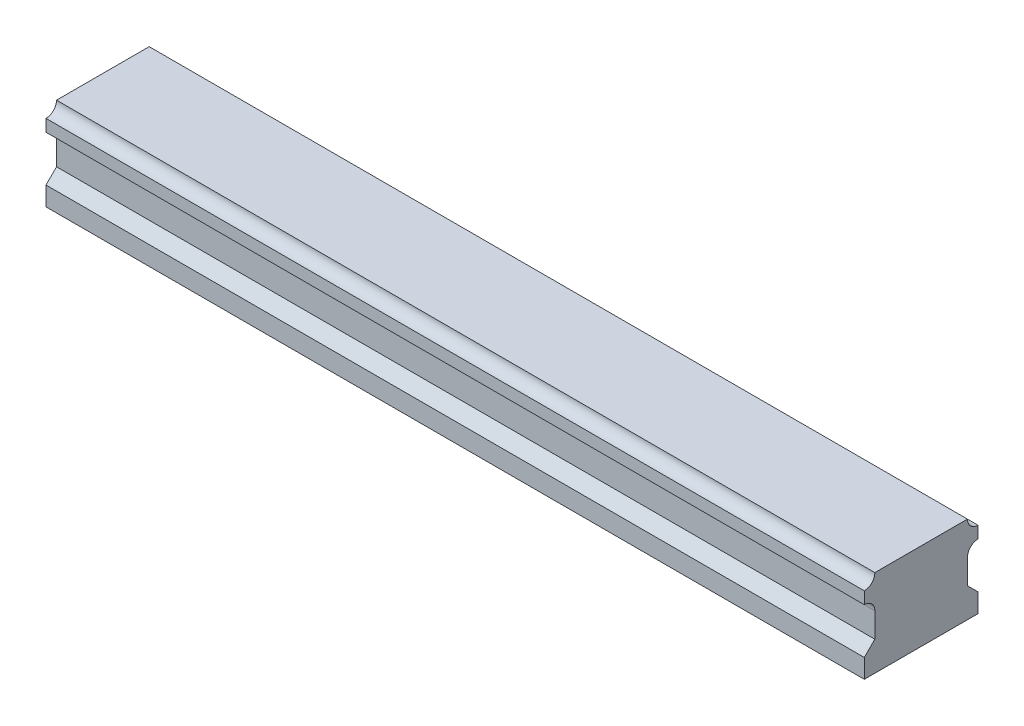
SolidWorks part; units mm, degrees
ref_plane "Front Plane" through (0, 0, 0) normal (0, 0, 1) x (1, 0, 0)
ref_plane "Top Plane" through (0, 0, 0) normal (0, 1, 0) x (1, 0, 0)
ref_plane "Right Plane" through (0, 0, 0) normal (1, 0, 0) x (0, 0, -1)
sketch "Sketch1" plane through (0, 0, 0) normal (1, 0, 0) x (0, 0, -1)
  line L0 (0, 0) -> (30, 0)
  line L1 (0, 0) -> (0, 5)
  line L2 (0, 5) -> (2.7781, 7.7781)
  line L3 (2.7781, 7.7781) -> (2.7781, 14.2781)
  line L4 (2.7781, 14.2781) -> (0, 14.2781) construction
  line L5 (0, 14.2781) -> (0, 23) construction
  line L6 (0, 23) -> (30, 23) construction
  line L12 (15, 0) -> (15, 23) construction
  line L13 (27.2219, 23) -> (2.7781, 23)
  line L14 (0, 20.2219) -> (0, 17.0562)
  line L15 (30, 14.2781) -> (30, 23) construction
  line L16 (27.2219, 14.2781) -> (30, 14.2781) construction
  line L17 (30, 20.2219) -> (30, 17.0562)
  line L18 (27.2219, 7.7781) -> (27.2219, 14.2781)
  line L19 (30, 5) -> (27.2219, 7.7781)
  line L20 (30, 0) -> (30, 5)
  arc A0 (2.7781, 14.2781) -> (0, 17.0562) centre (0, 14.2781) ccw
  arc A1 (0, 20.2219) -> (2.7781, 23) centre (0, 23) ccw
  arc A2 (30, 20.2219) -> (27.2219, 23) centre (30, 23) cw
  arc A3 (27.2219, 14.2781) -> (30, 17.0562) centre (30, 14.2781) cw
  dimension "D1" = 5.5563
  dimension "D2" = 15
  dimension "D3" = 23
  dimension "D4" = 45
  dimension "D5" = 6.5
  dimension "D6" = 5
extrude "Boss-Extrude1" add sketch "Sketch1" along normal blind 215.9
